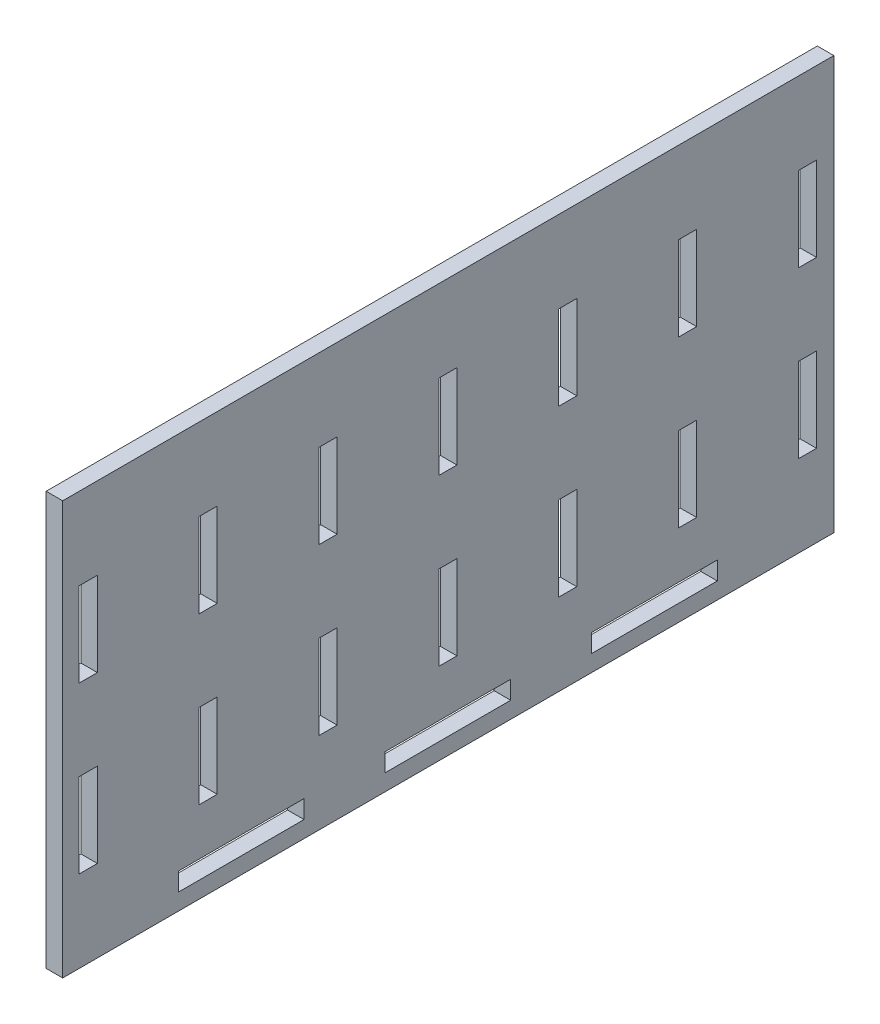
SolidWorks part; units mm, degrees
ref_plane "Спереди" through (0, 0, 0) normal (0, 0, 1) x (1, 0, 0)
ref_plane "Сверху" through (0, 0, 0) normal (0, 1, 0) x (1, 0, 0)
ref_plane "Справа" through (0, 0, 0) normal (1, 0, 0) x (0, 0, -1)
sketch "Эскиз1" plane through (0, 0, 0) normal (1, 0, 0) x (0, 0, -1)
  line L0 (4, 40.2) -> (4, 59.8) construction
  line L1 (0, 0) -> (186.6, 0)
  line L2 (0, 0) -> (0, 100)
  line L3 (0, 100) -> (186.6, 100)
  line L4 (186.6, 0) -> (186.6, 100)
  line L5 (4, 19.8) -> (8.4, 19.8)
  line L6 (4, 19.8) -> (4, 40.2)
  line L7 (4, 40.2) -> (8.4, 40.2)
  line L8 (8.4, 19.8) -> (8.4, 40.2)
  line L9 (4, 59.8) -> (8.4, 59.8)
  line L10 (4, 59.8) -> (4, 80.2)
  line L11 (4, 80.2) -> (8.4, 80.2)
  line L12 (8.4, 59.8) -> (8.4, 80.2)
  line L13 (8.4, 40.2) -> (8.4, 59.8) construction
  line L14 (8.4, 30) -> (24.8633, 30) construction
  line L15 (8.4, 70) -> (21.2086, 70) construction
  line L16 (37.4, 59.8) -> (37.4, 80.2)
  line L17 (33, 59.8) -> (37.4, 59.8)
  line L18 (33, 59.8) -> (33, 80.2)
  line L19 (33, 80.2) -> (37.4, 80.2)
  line L20 (33, 40.2) -> (37.4, 40.2)
  line L21 (33, 19.8) -> (33, 40.2)
  line L22 (37.4, 19.8) -> (37.4, 40.2)
  line L23 (33, 19.8) -> (37.4, 19.8)
  line L24 (66.4, 59.8) -> (66.4, 80.2)
  line L25 (62, 59.8) -> (66.4, 59.8)
  line L26 (62, 59.8) -> (62, 80.2)
  line L27 (62, 80.2) -> (66.4, 80.2)
  line L28 (62, 40.2) -> (66.4, 40.2)
  line L29 (62, 19.8) -> (62, 40.2)
  line L30 (66.4, 19.8) -> (66.4, 40.2)
  line L31 (62, 19.8) -> (66.4, 19.8)
  line L32 (95.4, 59.8) -> (95.4, 80.2)
  line L33 (91, 59.8) -> (95.4, 59.8)
  line L34 (91, 59.8) -> (91, 80.2)
  line L35 (91, 80.2) -> (95.4, 80.2)
  line L36 (91, 40.2) -> (95.4, 40.2)
  line L37 (91, 19.8) -> (91, 40.2)
  line L38 (95.4, 19.8) -> (95.4, 40.2)
  line L39 (91, 19.8) -> (95.4, 19.8)
  line L40 (124.4, 59.8) -> (124.4, 80.2)
  line L41 (120, 59.8) -> (124.4, 59.8)
  line L42 (120, 59.8) -> (120, 80.2)
  line L43 (120, 80.2) -> (124.4, 80.2)
  line L44 (120, 40.2) -> (124.4, 40.2)
  line L45 (120, 19.8) -> (120, 40.2)
  line L46 (124.4, 19.8) -> (124.4, 40.2)
  line L47 (120, 19.8) -> (124.4, 19.8)
  line L48 (153.4, 59.8) -> (153.4, 80.2)
  line L49 (149, 59.8) -> (153.4, 59.8)
  line L50 (149, 59.8) -> (149, 80.2)
  line L51 (149, 80.2) -> (153.4, 80.2)
  line L52 (149, 40.2) -> (153.4, 40.2)
  line L53 (149, 19.8) -> (149, 40.2)
  line L54 (153.4, 19.8) -> (153.4, 40.2)
  line L55 (149, 19.8) -> (153.4, 19.8)
  line L56 (182.4, 59.8) -> (182.4, 80.2)
  line L57 (178, 59.8) -> (182.4, 59.8)
  line L58 (178, 59.8) -> (178, 80.2)
  line L59 (178, 80.2) -> (182.4, 80.2)
  line L60 (178, 40.2) -> (182.4, 40.2)
  line L61 (178, 19.8) -> (178, 40.2)
  line L62 (182.4, 19.8) -> (182.4, 40.2)
  line L63 (178, 19.8) -> (182.4, 19.8)
  line L64 (8.4, 59.8) -> (37.4, 59.8) construction
  line L65 (8.4, 19.8) -> (33, 19.8) construction
  line L66 (0, 4) -> (28, 4) construction
  line L67 (58.4, 8.4) -> (78, 8.4) construction
  line L68 (28, 4) -> (58.4, 4)
  line L69 (28, 4) -> (28, 8.4)
  line L70 (28, 8.4) -> (58.4, 8.4)
  line L71 (58.4, 4) -> (58.4, 8.4)
  line L72 (78, 4) -> (108.4, 4)
  line L73 (78, 4) -> (78, 8.4)
  line L74 (78, 8.4) -> (108.4, 8.4)
  line L75 (108.4, 4) -> (108.4, 8.4)
  line L76 (128, 4) -> (158.4, 4)
  line L77 (128, 4) -> (128, 8.4)
  line L78 (128, 8.4) -> (158.4, 8.4)
  line L79 (158.4, 4) -> (158.4, 8.4)
  line L80 (58.4, 4) -> (78, 4) construction
  line L81 (108.4, 8.4) -> (128, 8.4) construction
  line L82 (108.4, 4) -> (128, 4) construction
  line L83 (43.2, 4) -> (43.2, -5.7298) construction
  line L84 (93.2, 4) -> (93.2, -5.7298) construction
  line L85 (143.2, 4) -> (143.2, -5.7298) construction
  dimension "D1" = 100
  dimension "D2" = 186.6
  dimension "D3" = 20.4
  dimension "D4" = 20.4
  dimension "D5" = 30
  dimension "D6" = 40
  dimension "D7" = 4
  dimension "D8" = 4.4
  dimension "D10" = 29
  dimension "D11" = 4
  dimension "D12" = 4.4
  dimension "D13" = 30.4
  dimension "D14" = 30.4
  dimension "D15" = 30.4
  dimension "D16" = 50
  dimension "D17" = 50
  dimension "D18" = 43.2
  dimension "D9" = 7
extrude "Бобышка-Вытянуть1" add sketch "Эскиз1" along normal blind 4
